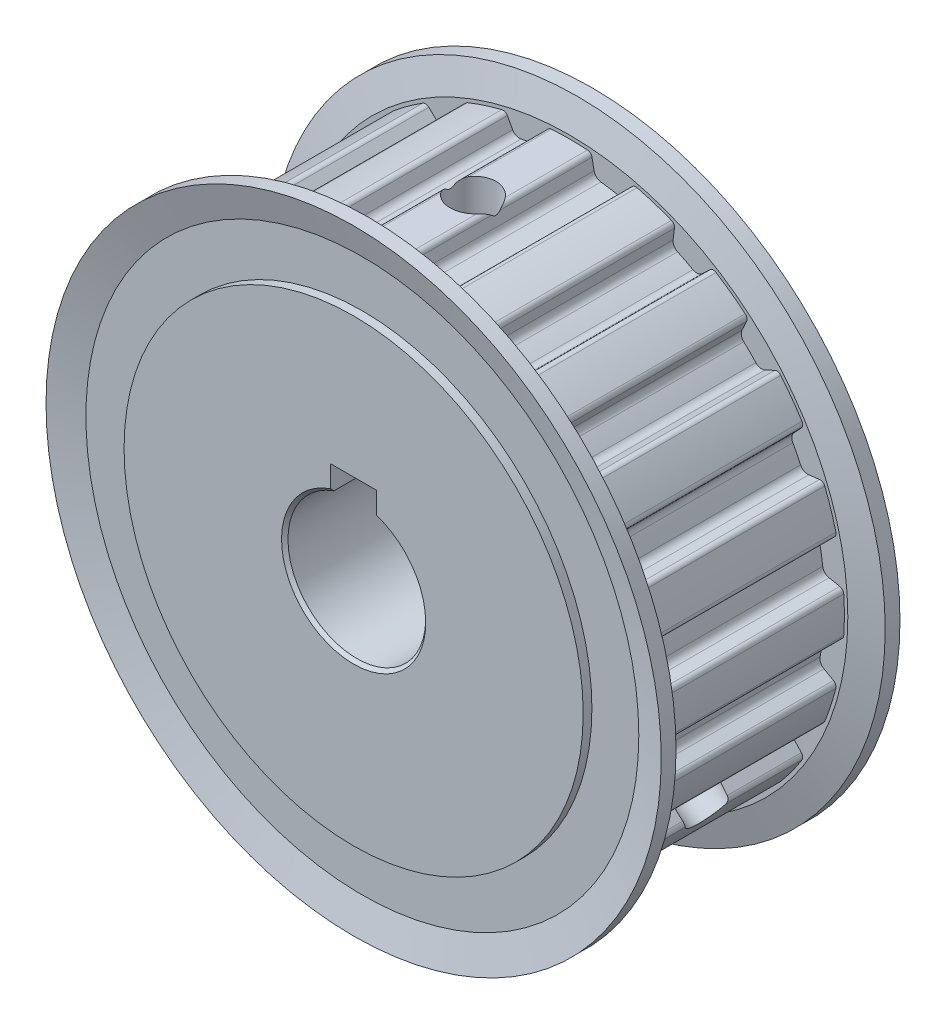
SolidWorks part; units mm, degrees
material "1060 合金"
ref_plane "前视基准面" through (0, 0, 0) normal (0, 0, 1) x (1, 0, 0)
ref_plane "上视基准面" through (0, 0, 0) normal (0, 1, 0) x (1, 0, 0)
ref_plane "右视基准面" through (0, 0, 0) normal (1, 0, 0) x (0, 0, -1)
sketch "草图1" plane through (0, 0, 0) normal (1, 0, 0) x (0, 0, -1)
  line L0 (-13, 0) -> (13, 0) construction
  line L1 (13, 0) -> (13, 25)
  line L2 (13, 25) -> (12.05, 25)
  line L3 (12.05, 25) -> (12.05, 30.1071)
  line L4 (12.05, 30.1071) -> (13, 33.5)
  line L5 (13, 33.5) -> (11.3904, 33.5)
  line L6 (11.3904, 33.5) -> (10.5, 30.32)
  line L7 (10.5, 30.32) -> (10.5, 29.94)
  line L8 (0, 0) -> (0, 33.5) construction
  line L9 (-25, 0) -> (-45, 0) construction
  line L10 (-25, 0) -> (-13, 0) construction
  line L11 (-13, 20) -> (-25, 20)
  line L12 (-25, 20) -> (-25, 0)
  line L13 (-18, 20) -> (-18, 0) construction
  point P10 (10.5, 29.94)
  dimension "D1" = 2.5
  dimension "W" = 26
  dimension "F" = 67
  dimension "D2" = 1.55
  dimension "E" = 50
  dimension "D3" = 1.55
  dimension "PD" = 60.64
  dimension "OD" = 59.88
  dimension "D4" = 7
  dimension "CS" = 20
  dimension "L" = 38
  dimension "D" = 40
sketch "草图2" plane through (0, 0, 0) normal (0, 0, 1) x (1, 0, 0)
  line L0 (0, 29.94) -> (0, -29.94) construction
  line L1 (-2.8062, 27.658) -> (-2.3811, 29.8452)
  line L2 (2.8062, 27.658) -> (2.3811, 29.8452)
  line L3 (5.8779, 27.1715) -> (6.9581, 29.1202)
  line L5 (0, 0) -> (4.3489, 27.4577) construction
  line L7 (2.8062, 27.658) -> (0, 0) construction
  line L8 (0, 0) -> (5.8779, 27.1715) construction
  arc A0 (2.3811, 29.8452) -> (-2.3811, 29.8452) centre (0, 0) ccw
  arc A1 (5.8779, 27.1715) -> (2.8062, 27.658) centre (0, 0) ccw
  circle A2 centre (0, 0) radius 27.8 construction
  circle A3 centre (2.1553, 29.5916) radius 0.27
  circle A4 centre (3.1677, 28.0517) radius 0.43
  point P6 (0, 27.8)
  dimension "D1" = 2.14
  dimension "D5" = 0.54
  dimension "D6" = 0.86
  dimension "D2" = 3.11
  dimension "CX" = 20
  dimension "D4" = 9
sketch "草图3" plane through (0, 0, 0) normal (1, 0, 0) x (0, 0, -1)
  line L0 (13, 0) -> (13, 25) construction
  line L1 (13, 25) -> (12.05, 25) construction
  line L2 (12.05, 25) -> (12.05, 30.1071) construction
  line L3 (12.05, 30.1071) -> (13, 33.5) construction
  line L4 (13, 33.5) -> (11.3904, 33.5) construction
  line L5 (11.3904, 33.5) -> (10.5, 30.32) construction
  line L7 (13, 0) -> (13, 25)
  line L8 (13, 25) -> (12.05, 25)
  line L9 (12.05, 25) -> (12.05, 30.1071)
  line L10 (12.05, 30.1071) -> (13, 33.5)
  line L11 (13, 33.5) -> (11.3904, 33.5)
  line L12 (11.3904, 33.5) -> (10.5, 30.32)
  line L13 (10.5, 30.32) -> (10.5, 27.8)
  line L15 (10.5, 27.8) -> (-10.5, 27.8)
  line L16 (0, 0) -> (0, 33.5) construction
  line L17 (0, 0) -> (0, 33.5) construction
  line L18 (-10.5, 30.32) -> (-10.5, 27.8)
  line L19 (-11.3904, 33.5) -> (-10.5, 30.32)
  line L20 (-13, 33.5) -> (-11.3904, 33.5)
  line L21 (-12.05, 30.1071) -> (-13, 33.5)
  line L22 (-12.05, 25) -> (-12.05, 30.1071)
  line L23 (-13, 25) -> (-12.05, 25)
  line L24 (-13, 0) -> (-13, 25)
  line L25 (-13, 0) -> (13, 0)
  point P14 (0, 27.8)
revolve "旋转1" add sketch "草图3" angle 360 about L0
sketch "草图4" plane through (0, 0, 0) normal (0, 0, 1) x (1, 0, 0)
  line L0 (-2.8062, 27.658) -> (-2.3811, 29.8452) construction
  line L1 (2.8062, 27.658) -> (2.3811, 29.8452) construction
  line L2 (-2.8062, 27.658) -> (-2.3811, 29.8452)
  line L3 (2.8062, 27.658) -> (2.3811, 29.8452)
  arc A0 (2.3811, 29.8452) -> (-2.3811, 29.8452) centre (0, 0) ccw construction
  arc A1 (2.3811, 29.8452) -> (-2.3811, 29.8452) centre (0, 0) ccw
  circle A2 centre (0, 0) radius 27.8 construction
  arc A3 (2.8062, 27.658) -> (-2.8062, 27.658) centre (0, 0) ccw
extrude "凸台-拉伸1" add sketch "草图4" along normal mid plane 21
fillet "圆角1" radius 0.54 2 edges at (-2.3811, 29.8452, 0) (2.3811, 29.8452, 0)
fillet "圆角2" radius 0.86 2 edges at (-2.8062, 27.658, 0) (2.8062, 27.658, 0)
pattern_circular "阵列(圆周)1" count 20 over 360 about axis through (0, 0, 0) along (0, 0, 1) of "凸台-拉伸1", "圆角1", "圆角2"
sketch "草图14" plane through (0, 0, 0) normal (1, 0, 0) x (0, 0, -1)
  line L0 (-13, 33.5) -> (-13, -33.5) construction
  line L1 (-25, 20) -> (-13, 20)
  line L2 (-25, 20) -> (-25, 0)
  line L3 (-25, 0) -> (-13, 0)
  line L4 (-13, 20) -> (-13, 0)
revolve "旋转2" [suppressed] add sketch "草图14" angle 360 about L3
sketch "草图H" plane through (0, 0, 0) normal (1, 0, 0) x (0, 0, -1)
  line L0 (13, 0) -> (13, 25) construction
  line L1 (-13, 0) -> (13, 0) construction
  line L2 (-13, 0) -> (13, 0) construction
  point P0 (13, 0.5)
  dimension "dH" = 1
sketch "草图6" [suppressed] plane through (0, 0, 0) normal (0, 0, 1) x (1, 0, 0)
  circle A0 centre (0, 0) radius 10
extrude "切除-拉伸1" [suppressed] cut sketch "草图6" against normal through all and the other way through all
chamfer "倒角1" [suppressed] distance 0.21 angle 45
sketch "草图P" plane through (0, 0, 0) normal (0, 0, 1) x (1, 0, 0)
  line L0 (0, 0) -> (0, 33.5) construction
  line L1 (0, 0) -> (0, 33.5) construction
  circle A0 centre (0, 0) radius 0.5
  point P3 (0.25, 0.433)
  dimension "dP" = 1
  dimension "MP" = 0.5
sketch "草图19" [suppressed] plane through (0, 0, 0) normal (0, 0, 1) x (1, 0, 0)
  circle A0 centre (0, 0) radius 2.5 construction
  circle A1 centre (0, 0) radius 2.5
extrude "切除-拉伸5" [suppressed] cut sketch "草图19" against normal through all and the other way through all
chamfer "倒角6" [suppressed] distance 0.05 angle 45
sketch "草图20" [suppressed] plane through (0, 0, 0) normal (0, 1, 0) x (1, 0, 0)
  line L0 (0, -25) -> (0, -13) construction
  circle A0 centre (0, 0) radius 1.5
  point P4 (1.5, 0)
extrude "切除-拉伸6" [suppressed] cut sketch "草图20" along normal through all
cosmetic thread "装饰螺纹线3" [suppressed] parameters "D2"=0.6
ref_plane "基准面2" [suppressed] through (0, 0, 0) normal (-0.866, 0.5, 0) x (-0.5, -0.866, 0)
sketch "草图21" [suppressed] plane through (0, 0, 0) normal (-0.866, 0.5, 0) x (-0.5, -0.866, 0)
  circle A0 centre (0, 0) radius 1.5
  dimension "D1" = 0.5
extrude "切除-拉伸7" [suppressed] cut sketch "草图21" against normal through all
cosmetic thread "装饰螺纹线4" [suppressed] parameters "D2"=0.6
chamfer "倒角7" [suppressed] distance 0.035 angle 45
sketch "草图N" plane through (0, 0, 0) normal (0, 0, 1) x (1, 0, 0)
  line L0 (-2.5, 7.0711) -> (-2.5, 9.8)
  line L1 (-2.5, 9.8) -> (2.5, 9.8)
  line L2 (2.5, 9.8) -> (2.5, 7.0711)
  line L3 (0, 0) -> (0, 33.5) construction
  line L4 (0, 0) -> (0, 33.5) construction
  arc A0 (-2.5, 7.0711) -> (2.5, 7.0711) centre (0, 0) ccw
  point P1 (0, 7.5)
  point P8 (2.5, 9.8)
  dimension "dN" = 15
  dimension "bN" = 5
  dimension "tN" = 2.3
  dimension "MN" = 5
sketch "草图9" plane through (0, 0, 0) normal (0, 0, 1) x (1, 0, 0)
  line L0 (-2.5, 7.0711) -> (-2.5, 9.8) construction
  line L1 (-2.5, 9.8) -> (2.5, 9.8) construction
  line L2 (2.5, 9.8) -> (2.5, 7.0711) construction
  line L3 (-2.5, 7.0711) -> (-2.5, 9.8)
  line L4 (-2.5, 9.8) -> (2.5, 9.8)
  line L5 (2.5, 9.8) -> (2.5, 7.0711)
  arc A0 (-2.5, 7.0711) -> (2.5, 7.0711) centre (0, 0) ccw construction
  arc A1 (-2.5, 7.0711) -> (2.5, 7.0711) centre (0, 0) ccw
extrude "切除-拉伸2" cut sketch "草图9" against normal through all and the other way through all
chamfer "倒角2" distance 0.35 angle 45 2 edges at (0, -7.5, -13) (0, -7.5, 13)
sketch "草图15" plane through (0, 0, 0) normal (0, 1, 0) x (1, 0, 0)
  circle A0 centre (0, 0) radius 2.5
  point P2 (2.5, 0)
extrude "切除-拉伸3" cut sketch "草图15" along normal through all from vertex at 9.8 starting at point (2.5, 9.8, 0)
cosmetic thread "装饰螺纹线1" parameters "D2"=5.1
ref_plane "基准面1" through (0, 0, 0) normal (-0.866, 0.5, 0) x (-0.5, -0.866, 0)
sketch "草图16" plane through (0, 0, 0) normal (-0.866, 0.5, 0) x (-0.5, -0.866, 0)
  circle A0 centre (0, 0) radius 2.5
  dimension "D1" = 5
extrude "切除-拉伸4" cut sketch "草图16" against normal through all
cosmetic thread "装饰螺纹线2" parameters "D2"=5.1
chamfer "倒角5" [suppressed] distance 0.25 angle 45
sketch "草图V" plane through (0, 0, 0) normal (1, 0, 0) x (0, 0, -1)
  line L0 (-13, 0.5) -> (11, 0.5)
  line L1 (11, 0.5) -> (11, 1.5)
  line L2 (11, 1.5) -> (13, 1.5)
  line L3 (-13, 0) -> (13, 0) construction
  line L4 (-13, 0) -> (13, 0) construction
  dimension "dV" = 1
  dimension "ZV" = 3
  dimension "JV" = 2
sketch "草图11" [suppressed] plane through (0, 0, 0) normal (1, 0, 0) x (0, 0, -1)
  line L1 (9, 4) -> (9, 5) construction
  line L2 (9, 5) -> (13, 5) construction
  line L3 (-13, 4) -> (9, 4)
  line L4 (9, 4) -> (9, 5)
  line L5 (9, 5) -> (13, 5)
  line L6 (-13, 4) -> (-13, 0)
  line L7 (-13, 0) -> (13, 0)
  line L8 (13, 0) -> (13, 5)
revolve "切除-旋转1" [suppressed] cut sketch "草图11" angle 360 about L0
chamfer "倒角3" [suppressed] distance 0.13 angle 45
sketch "草图F" plane through (0, 0, 0) normal (1, 0, 0) x (0, 0, -1)
  line L0 (-13, 0) -> (13, 0) construction
  line L3 (-13, 0) -> (13, 0) construction
  line L4 (-13, 0) -> (-13, 5)
  line L5 (-13, 33.5) -> (-13, -33.5) construction
  line L8 (-13, 5) -> (-9, 5)
  line L9 (-9, 5) -> (-9, 4)
  line L10 (-9, 4) -> (13, 4)
  line L11 (13, 4) -> (13, 0)
  dimension "ZF" = 10
  dimension "dF" = 8
  dimension "JF" = 4
sketch "草图22" [suppressed] plane through (0, 0, 0) normal (1, 0, 0) x (0, 0, -1)
  line L0 (-11.5, 0) -> (-11.5, 5)
  line L2 (-11.5, 7) -> (-11.5, 0) construction
  line L3 (-11.5, 5) -> (-7.5, 5)
  line L4 (-5, 5) -> (-1, 5) construction
  line L6 (-7.5, 5) -> (-7.5, 4)
  line L9 (5, 4) -> (5, 0)
  line L10 (5, 0) -> (-11.5, 0)
  line L11 (-7.5, 4) -> (5, 4)
revolve "切除-旋转3" [suppressed] cut sketch "草图22" angle 360 about L10
chamfer "倒角8" [suppressed] distance 0.18 angle 45
sketch "草图Y" plane through (0, 0, 0) normal (1, 0, 0) x (0, 0, -1)
  line L2 (-13, 0) -> (13, 0) construction
  line L3 (-13, 0) -> (13, 0) construction
  line L4 (-13, 1.5) -> (-10, 1.5)
  line L5 (-10, 1.5) -> (-10, 0.5)
  line L6 (-10, 0.5) -> (10, 0.5)
  line L7 (10, 0.5) -> (10, 1.5)
  line L8 (10, 1.5) -> (13, 1.5)
  dimension "dY" = 1
  dimension "QY" = 3
  dimension "RY" = 3
  dimension "SY" = 3
  dimension "TY" = 3
sketch "草图13" [suppressed] plane through (0, 0, 0) normal (1, 0, 0) x (0, 0, -1)
  line L0 (-9.5, 4) -> (-6.5, 4) construction
  line L1 (-6.5, 4) -> (-6.5, 2.5) construction
  line L2 (-6.5, 2.5) -> (6.5, 2.5) construction
  line L3 (6.5, 2.5) -> (6.5, 4.5) construction
  line L4 (6.5, 4.5) -> (9.5, 4.5) construction
  line L5 (-9.5, 4) -> (-6.5, 4)
  line L6 (-6.5, 4) -> (-6.5, 2.5)
  line L7 (-6.5, 2.5) -> (6.5, 2.5)
  line L8 (6.5, 2.5) -> (6.5, 4.5)
  line L9 (6.5, 4.5) -> (9.5, 4.5)
  line L10 (-9.5, 4) -> (-9.5, 0)
  line L11 (-9.5, 0) -> (9.5, 0)
  line L12 (9.5, 0) -> (9.5, 4.5)
revolve "切除-旋转2" [suppressed] cut sketch "草图13" angle 360 about L0
chamfer "倒角4" [suppressed] distance 0.0067 angle 45
sketch "草图23" [suppressed] plane through (0, 0, 0) normal (0, 0, 1) x (1, 0, 0)
  line L0 (0, 5) -> (0, 0) construction
  line L1 (-2, 6.8) -> (2, 6.8)
  line L2 (-2, 6.8) -> (-2, 4.5826)
  line L4 (2, 6.8) -> (2, 4.5826)
  arc A0 (-2, 4.5826) -> (2, 4.5826) centre (0, 0) ccw
  circle A2 centre (0, 0) radius 5 construction
  dimension "D1" = 10
  dimension "D2" = 4
  dimension "D3" = 1.8
extrude "切除-拉伸8" [suppressed] cut sketch "草图23" against normal through all and the other way through all
chamfer "倒角9" [suppressed] distance 0.3 angle 45
sketch "草图24" [suppressed] plane through (0, 0, 0) normal (0, 1, 0) x (1, 0, 0)
  circle A0 centre (0, 0) radius 2
  dimension "D1" = 4
extrude "切除-拉伸9" [suppressed] cut sketch "草图24" along normal through all
cosmetic thread "装饰螺纹线5" [suppressed] parameters "D2"=4.1
pattern_circular "阵列(圆周)2" [suppressed] count 2 over 120
sketch "草图26" plane through (0, 0, 0) normal (1, 0, 0) x (0, 0, -1)
  line L0 (0, 0) -> (0, 33.5) construction
  line L1 (12.05, 25) -> (12.05, 30.1071)
  line L2 (12.05, 30.1071) -> (13, 33.5)
  line L3 (13, 33.5) -> (11.3904, 33.5)
  line L4 (11.3904, 33.5) -> (10.5, 30.32)
  line L5 (10.5, 30.32) -> (10.5, 25)
  line L6 (10.5, 25) -> (12.05, 25)
  line L7 (0, 0) -> (0, 33.5) construction
  line L8 (-10.5, 25) -> (-12.05, 25)
  line L9 (-10.5, 30.32) -> (-10.5, 25)
  line L10 (-11.3904, 33.5) -> (-10.5, 30.32)
  line L11 (-13, 33.5) -> (-11.3904, 33.5)
  line L12 (-12.05, 30.1071) -> (-13, 33.5)
  line L13 (-12.05, 25) -> (-12.05, 30.1071)
revolve "6072" [suppressed] cut sketch "草图26" angle 360 about L0
